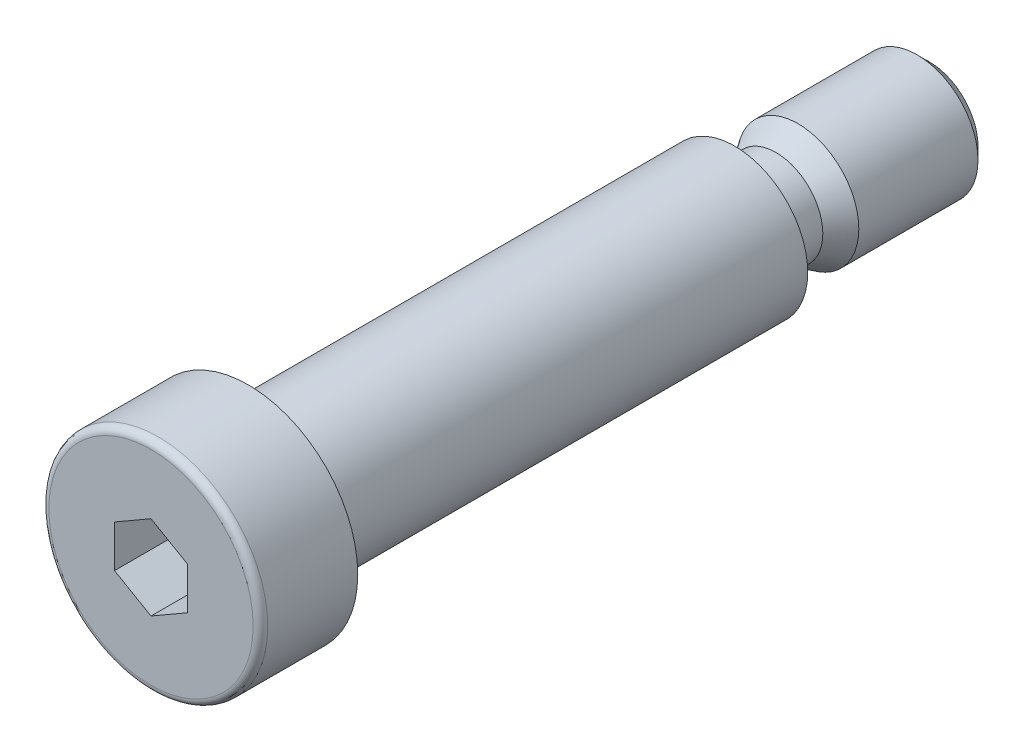
SolidWorks part; units mm, degrees
material "1.0545 (S355N)"
ref_plane "Płaszczyzna przednia" through (0, 0, 0) normal (0, 0, 1) x (1, 0, 0)
ref_plane "Płaszczyzna górna" through (0, 0, 0) normal (0, 1, 0) x (1, 0, 0)
ref_plane "Płaszczyzna prawa" through (0, 0, 0) normal (1, 0, 0) x (0, 0, -1)
sketch "Szkic1" plane through (0, 0, 0) normal (0, 1, 0) x (1, 0, 0)
  line L0 (5, 25.2) -> (3.85, 23.39)
  line L1 (9, -28) -> (-9, -28)
  line L2 (9, -28) -> (9, -20)
  line L3 (9, -20) -> (-9, -20)
  line L4 (-9, -28) -> (-9, -20)
  line L5 (6, -20) -> (-6, -20)
  line L6 (6, -20) -> (6, 20)
  line L7 (6, 20) -> (-6, 20)
  line L8 (-6, -20) -> (-6, 20)
  line L9 (-3.85, 20) -> (3.85, 20)
  line L10 (-3.85, 20) -> (-3.85, 23.39)
  line L11 (-3.85, 23.39) -> (3.85, 23.39)
  line L12 (3.85, 20) -> (3.85, 23.39)
  line L13 (5, 25.2) -> (5, 35)
  line L14 (5, 35) -> (4, 36)
  line L15 (4, 36) -> (-4, 36)
  line L16 (-4, 36) -> (-5, 35)
  line L17 (-5, 35) -> (-5, 25.2)
  line L18 (-5, 25.2) -> (-3.85, 23.39)
  line L19 (5, 25.2) -> (-5, 25.2) construction
  line L20 (5, 35) -> (-5, 35) construction
  line L21 (0, -19.9356) -> (0, 25.6583) construction
  line L22 (0, -28) -> (0, 36)
  point P4 (0, -20)
  point P14 (0, -20)
  point P15 (0, 20)
  point P16 (0, 20)
  point P17 (-6, 0)
  point P23 (0, 25.2)
  point P25 (0, 36)
  point P26 (0, 23.39)
  point P27 (0, 35)
  dimension "D1" = 18
  dimension "D2" = 8
  dimension "D3" = 12
  dimension "l1" = 40
  dimension "D5" = 7.7
  dimension "D6" = 16
  dimension "D7" = 10
  dimension "D8" = 8
  dimension "D9" = 1
  dimension "D10" = 1.81
  dimension "D11" = 9.8
revolve "Obrót1" add sketch "Szkic1" angle 360 about L22
sketch "Szkic2" plane through (0, 0, 28) normal (0, 0, 1) x (1, 0, 0)
  line L1 (3, 1.7321) -> (0, 3.4641)
  line L2 (0, 3.4641) -> (-3, 1.7321)
  line L3 (-3, 1.7321) -> (-3, -1.7321)
  line L4 (-3, -1.7321) -> (0, -3.4641)
  line L5 (0, -3.4641) -> (3, -1.7321)
  line L6 (3, -1.7321) -> (3, 1.7321)
  circle A0 centre (0, 0) radius 3 construction
  dimension "D1" = 6
extrude "Wytnij-wyciągnięcie1" cut sketch "Szkic2" against normal blind 4.9
fillet "Zaokrąglenie1" radius 0.6 1 edges at (9, 0, 28)
